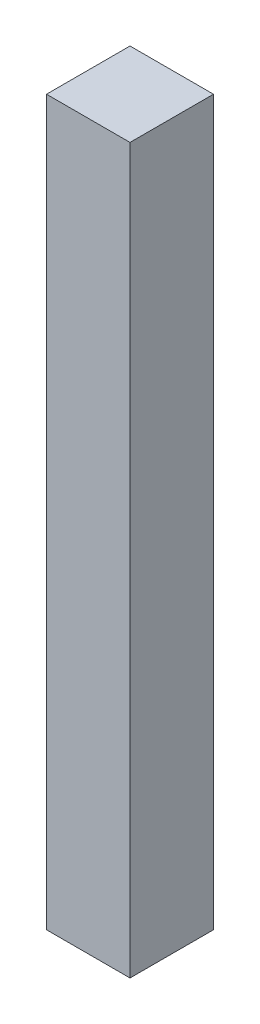
SolidWorks part; units mm, degrees
ref_plane "Front Plane" through (0, 0, 0) normal (0, 0, 1) x (1, 0, 0)
ref_plane "Top Plane" through (0, 0, 0) normal (0, 1, 0) x (1, 0, 0)
ref_plane "Right Plane" through (0, 0, 0) normal (1, 0, 0) x (0, 0, -1)
sketch "Sketch1" plane through (0, 0, 0) normal (0, 1, 0) x (1, 0, 0)
  line L1 (0, 0) -> (38.1, 0)
  line L2 (0, 0) -> (0, -38.1)
  line L3 (0, -38.1) -> (38.1, -38.1)
  line L4 (38.1, 0) -> (38.1, -38.1)
  dimension "D1" = 38.1
  dimension "D2" = 38.1
extrude "Boss-Extrude1" add sketch "Sketch1" along normal blind 330.2
